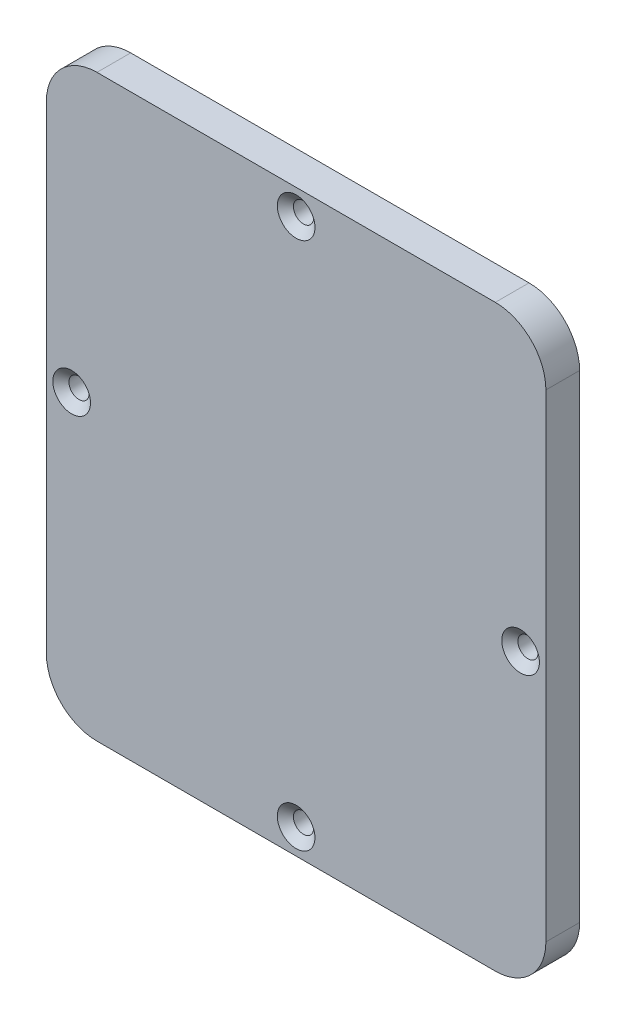
SolidWorks part; units mm, degrees
ref_plane "Front Plane" through (0, 0, 0) normal (0, 0, 1) x (1, 0, 0)
ref_plane "Top Plane" through (0, 0, 0) normal (0, 1, 0) x (1, 0, 0)
ref_plane "Right Plane" through (0, 0, 0) normal (1, 0, 0) x (0, 0, -1)
sketch "Sketch1" plane through (0, 0, 0) normal (0, 0, 1) x (1, 0, 0)
  line L8 (3.175, -6.35) -> (78.175, -6.35)
  line L9 (87.7, 3.175) -> (87.7, 93.175)
  line L10 (78.175, 102.7) -> (3.175, 102.7)
  line L11 (-6.35, 93.175) -> (-6.35, 3.175)
  circle A2 centre (-1.5875, 48.175) radius 1.5875
  circle A5 centre (40.675, -1.5875) radius 1.5875
  circle A6 centre (82.9375, 48.175) radius 1.5875
  circle A7 centre (40.675, 97.9375) radius 1.5875
  arc A16 (-6.35, 3.175) -> (3.175, -6.35) centre (3.175, 3.175) ccw
  arc A17 (78.175, -6.35) -> (87.7, 3.175) centre (78.175, 3.175) ccw
  arc A18 (87.7, 93.175) -> (78.175, 102.7) centre (78.175, 93.175) ccw
  arc A19 (3.175, 102.7) -> (-6.35, 93.175) centre (3.175, 93.175) ccw
extrude "Boss-Extrude1" add sketch "Sketch1" along normal blind 6.35
hole_wizard "CSK for #6 Flat Head Machine Screw (100)1" positions "Sketch2" profile "Sketch3" countersink size "#6" standard "ANSI Inch" end condition through all
sketch "Sketch2" plane through (0, 0, 6.35) normal (0, 0, 1) x (1, 0, 0)
  point P0 (82.9375, 48.175)
  point P3 (-1.5875, 48.175)
  point P6 (40.675, -1.5875)
  point P9 (40.675, 97.9375)
sketch "Sketch3" plane through (82.9375, 48.175, 6.35) normal (1, 0, 0) x (0, -1, 0)
  line L0 (0, 0) -> (0, 6.35)
  line L1 (0, 6.35) -> (1.8986, 6.35)
  line L2 (1.8986, 6.35) -> (1.8986, 1.38)
  line L3 (1.8986, 1.38) -> (3.5433, 0)
  line L5 (3.5433, 0) -> (0, 0)
  line L6 (-1.8986, 1.38) -> (-3.5433, 0) construction
  line L11 (0, -6.35) -> (0, 107.95) construction
  dimension "Thru Hole Dia." = 3.7973
  dimension "Thru Hole Depth" = 6.35
  dimension "Near C'Sink Dia." = 7.0866
  dimension "Near C'Sink Angle" = 100
